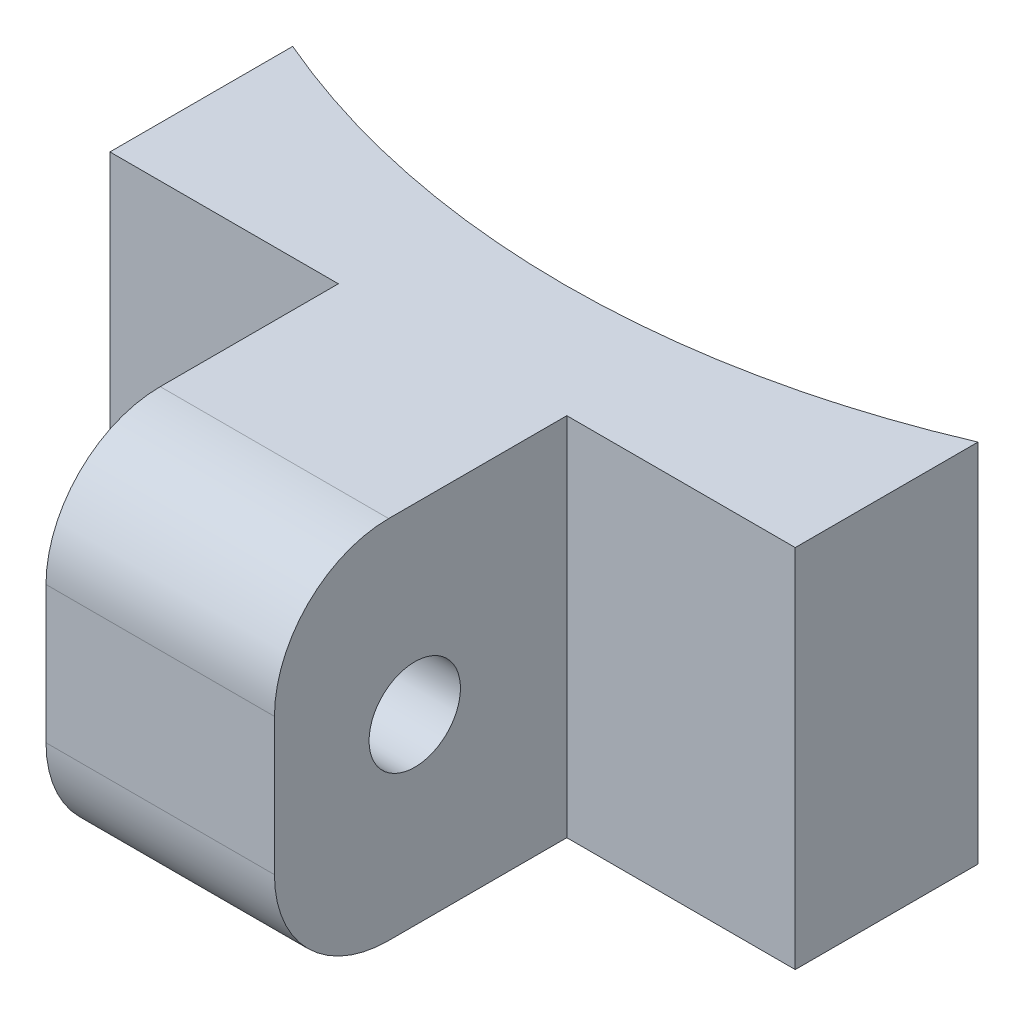
SolidWorks part; units mm, degrees
ref_plane "Спереди" through (0, 0, 0) normal (0, 0, 1) x (1, 0, 0)
ref_plane "Сверху" through (0, 0, 0) normal (0, 1, 0) x (1, 0, 0)
ref_plane "Справа" through (0, 0, 0) normal (1, 0, 0) x (0, 0, -1)
sketch "Эскиз1" plane through (0, 0, 0) normal (0, 1, 0) x (1, 0, 0)
  line L0 (0, 0) -> (0, -55.4959) construction
  line L1 (-15, -34.9142) -> (-15, -42.9142)
  line L2 (15, -34.9142) -> (15, -42.9142)
  line L3 (-15, -42.9142) -> (15, -42.9142)
  arc A0 (-15, -34.9142) -> (15, -34.9142) centre (0, 0) ccw
  circle A1 centre (0, 0) radius 38 construction
  dimension "D1" = 15
  dimension "D2" = 15
  dimension "D3" = 8
extrude "Вытянуть1" add sketch "Эскиз1" along normal blind 16 from offset 6
sketch "Эскиз2" plane through (0, 0, 0) normal (1, 0, 0) x (0, 0, -1)
  line L0 (-42.9142, 22) -> (-42.9142, 6) construction
  line L1 (-42.9142, 22) -> (-50.7129, 22)
  line L2 (-42.9142, 22) -> (-42.9142, 6)
  line L3 (-42.9142, 6) -> (-50.7129, 6)
  line L4 (-55.7129, 17) -> (-55.7129, 11)
  arc A0 (-55.7129, 17) -> (-50.7129, 22) centre (-50.7129, 17) cw
  arc A1 (-50.7129, 6) -> (-55.7129, 11) centre (-50.7129, 11) cw
  point P0 (-42.9142, 14)
  dimension "D1" = 5
extrude "Вытянуть2" add sketch "Эскиз2" along normal mid plane 10
sketch "Эскиз3" plane through (-5, 0, 0) normal (-1, 0, 0) x (0, 0, 1)
  circle A0 centre (49.5713, 14) radius 2
extrude "Вырез-Вытянуть1" cut sketch "Эскиз3" against normal mid plane 30
